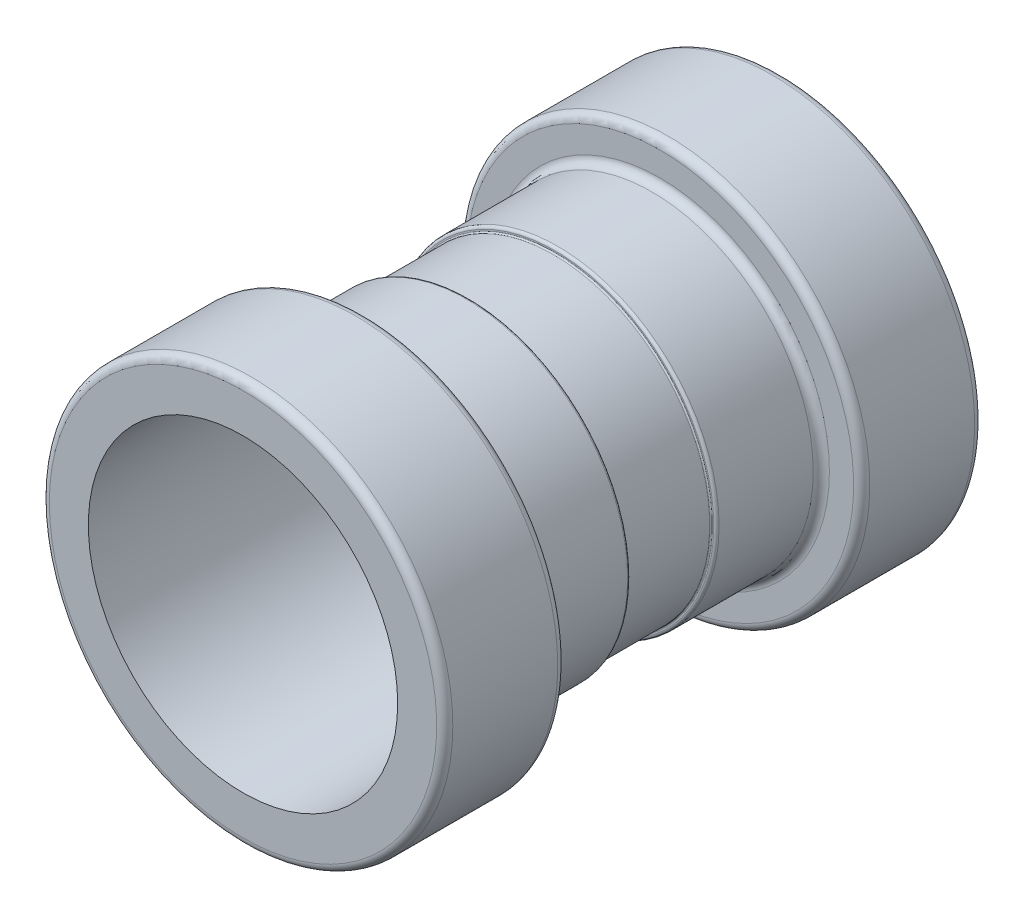
SolidWorks part; units mm, degrees
material "AISI 1020"
ref_plane "Ön Düzlem" through (0, 0, 0) normal (0, 0, 1) x (1, 0, 0)
ref_plane "Üst Düzlem" through (0, 0, 0) normal (0, 1, 0) x (1, 0, 0)
ref_plane "Sağ Düzlem" through (0, 0, 0) normal (1, 0, 0) x (0, 0, -1)
sketch "Çizim1" plane through (0, 0, 0) normal (1, 0, 0) x (0, 0, -1)
  line L0 (15.5, 58) -> (-15.5, 58)
  line L1 (55, 63) -> (55, 72)
  line L2 (58, 75) -> (97, 75)
  line L3 (0, 0) -> (212.3884, 0) construction
  line L4 (0, 88.928) -> (0, -95.2099) construction
  line L5 (-97, 75) -> (-58, 75)
  line L6 (-55, 72) -> (-55, 63)
  line L7 (100, 72) -> (100, 0)
  line L8 (-17, 60) -> (-52, 60)
  line L9 (-16, 58.5) -> (-16, 59)
  line L10 (-100, 72) -> (-100, 0)
  line L11 (0, 0) -> (-201.6865, 0) construction
  line L12 (100, 0) -> (-100, 0)
  line L15 (16, 58.5) -> (16, 59)
  line L16 (17, 60) -> (52, 60)
  arc A0 (58, 75) -> (55, 72) centre (58, 72) ccw
  arc A1 (100, 72) -> (97, 75) centre (97, 72) ccw
  arc A2 (-97, 75) -> (-100, 72) centre (-97, 72) ccw
  arc A3 (-58, 75) -> (-55, 72) centre (-58, 72) cw
  arc A4 (52, 60) -> (55, 63) centre (52, 63) ccw
  arc A5 (15.5, 58) -> (16, 58.5) centre (15.5, 58.5) ccw
  arc A6 (-16, 59) -> (-17, 60) centre (-17, 59) ccw
  arc A7 (-15.5, 58) -> (-16, 58.5) centre (-15.5, 58.5) cw
  arc A8 (-55, 63) -> (-52, 60) centre (-52, 63) ccw
  arc A10 (16, 59) -> (17, 60) centre (17, 59) cw
  point P14 (100, 75)
  point P15 (150, 124.5)
  point P18 (-100, 75)
  point P23 (-16, 60)
  point P25 (16, 58)
  point P35 (55, 60)
  point P37 (0, 46)
  point P38 (0, 12)
  point P40 (0, 56)
  point P42 (-55, 60)
  point P49 (16, 60)
  point P54 (0, 56.6826)
  point P58 (0, 58)
  point P59 (-16, 58)
  point P60 (-150, 124.5)
  dimension "D7" = 75
  dimension "D10" = 0.5
  dimension "D12" = 2
  dimension "D3" = 100
  dimension "D4" = 3
  dimension "D6" = 3
  dimension "D13" = 1
  dimension "D5" = 3
  dimension "D1" = 55
  dimension "D2" = 60
revolve "Döndür3" add sketch "Çizim1" angle 360 about L11
sketch "Çizim2" plane through (0, 0, 100) normal (0, 0, 1) x (1, 0, 0)
  circle A0 centre (0, 0) radius 57.5
  dimension "D1" = 115
extrude "Kes-Ekstrüzyon1" cut sketch "Çizim2" against normal through all contours A0
